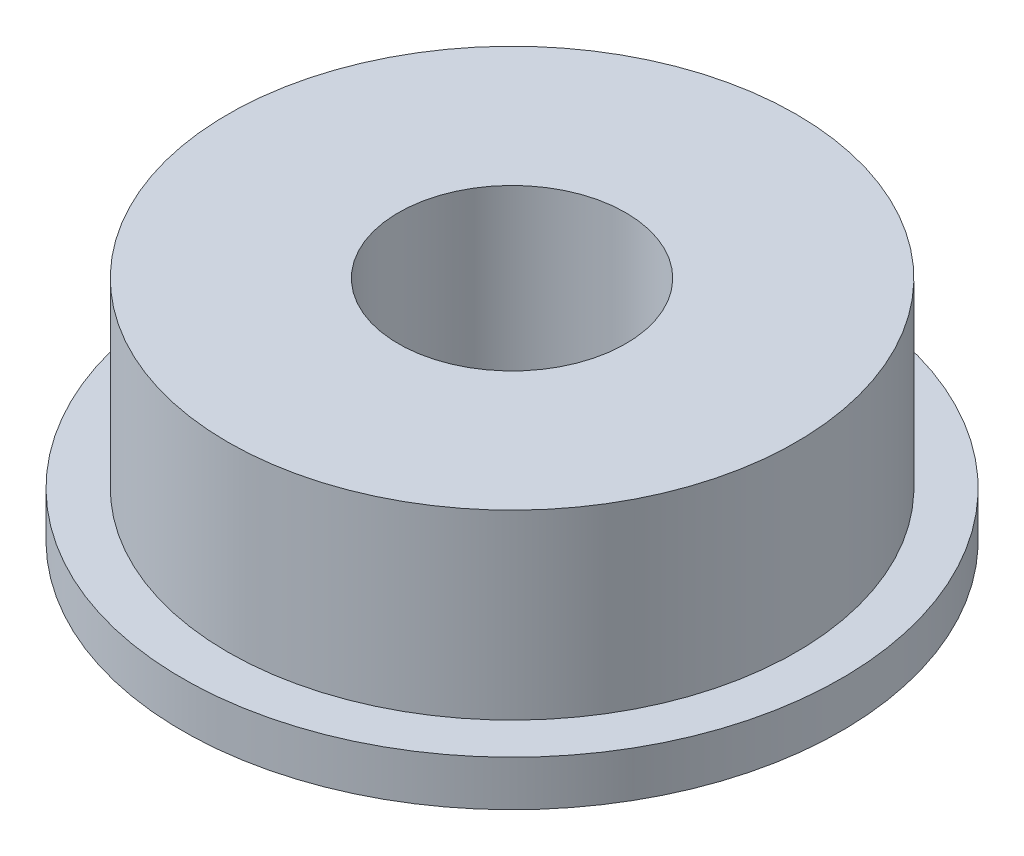
SolidWorks part; units mm, degrees
ref_plane "前视基准面" through (0, 0, 0) normal (0, 0, 1) x (1, 0, 0)
ref_plane "上视基准面" through (0, 0, 0) normal (0, 1, 0) x (1, 0, 0)
ref_plane "右视基准面" through (0, 0, 0) normal (1, 0, 0) x (0, 0, -1)
sketch "草图1" plane through (0, 0, 0) normal (0, 0, 1) x (1, 0, 0)
  line L0 (0, 0) -> (0, 29.6566) construction
  line L1 (2, 4) -> (2, 0)
  line L2 (2, 0) -> (5.8, 0)
  line L3 (5.8, 0) -> (5.8, 0.8)
  line L4 (5.8, 0.8) -> (5, 0.8)
  line L5 (5, 0.8) -> (5, 4)
  line L6 (5, 4) -> (2, 4)
  dimension "D1" = 11.6
  dimension "D2" = 0.8
  dimension "D3" = 4
  dimension "D4" = 4
  dimension "D5" = 10
revolve "旋转1" add sketch "草图1" angle 360 about L0
